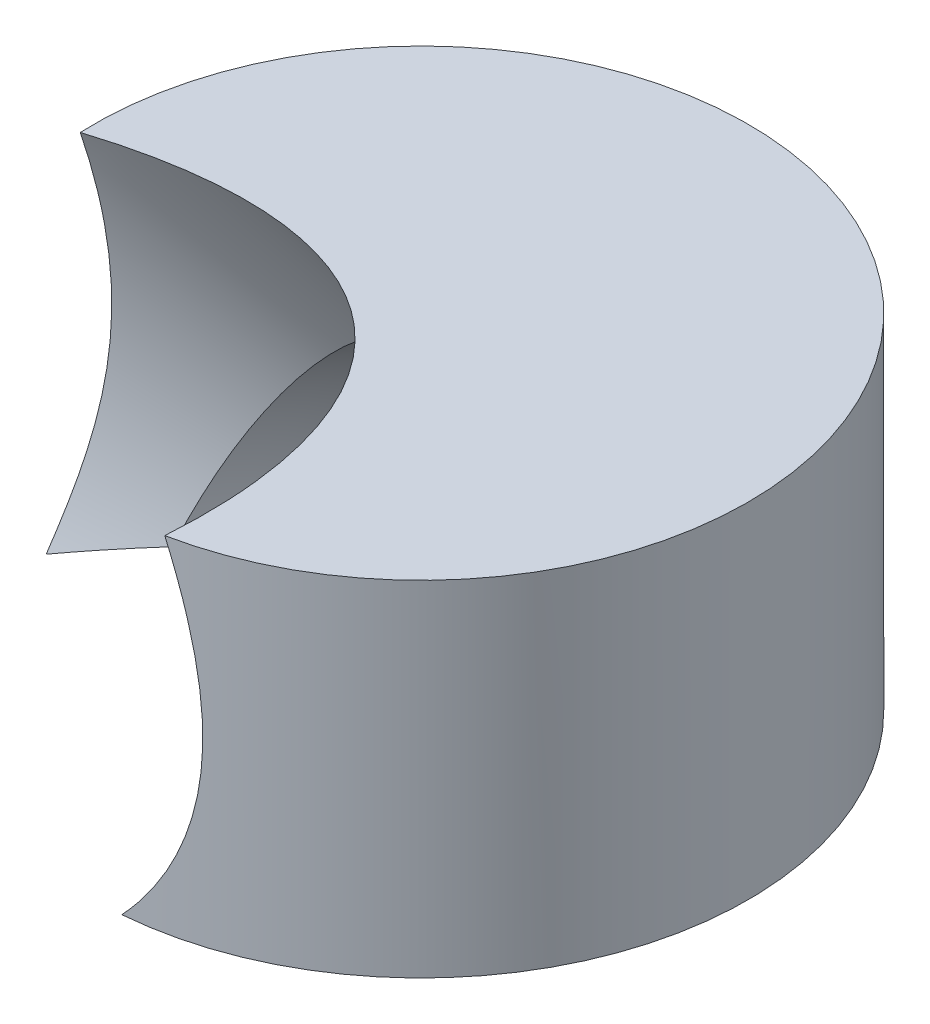
SolidWorks part; units mm, degrees
other "Moving Steel Cup Liner 2"
ref_plane "Front Plane" through (0, 0, 0) normal (0, 0, 1) x (1, 0, 0)
ref_plane "Top Plane" through (0, 0, 0) normal (0, 1, 0) x (1, 0, 0)
ref_plane "Right Plane" through (0, 0, 0) normal (1, 0, 0) x (0, 0, -1)
sketch3d "Keyed Back Sketch datum points"
  point P0 (-56.2917, -97, 0)
  point P1 (-46.2917, -97, 0)
  point P2 (-56.2917, -97, 10)
ref_plane "Keyed Back Sketch plane" through (0, -97, 0) normal (0, -1, 0) x (-1, 0, 0)
sketch "Keyed Back Sketch" plane through (0, -97, 0) normal (0, -1, 0) x (-1, 0, 0)
  line L0 (29.791, 11.2357) -> (33.8308, 13.5681)
  arc A0 (33.8308, 13.5681) -> (29.791, 11.2357) centre (30.3109, 15) ccw
extrude "Keyed Back" add sketch "Keyed Back Sketch" along normal blind 0.7 separate body
sketch3d "Cup Blank Sketch datum points"
  point P0 (-56.2917, -97.7, 0)
  point P1 (-46.2917, -97.7, 0)
  point P2 (-56.2917, -97.7, 10)
ref_plane "Cup Blank Sketch plane" through (0, -97.7, 0) normal (0, -1, 0) x (-1, 0, 0)
sketch "Cup Blank Sketch" plane through (0, -97.7, 0) normal (0, -1, 0) x (-1, 0, 0)
  circle A0 centre (30.3109, 15) radius 3.8
extrude "Cup Blank" add sketch "Cup Blank Sketch" along normal blind 3.3
sketch3d "Spherical Bearing Seat axis line"
  line L0 (-30.3109, -101, -25) -> (-30.3109, -101, -5) construction
ref_axis "Spherical Bearing Seat axis" through (-30.3109, -101, -25) along (0, 0, 1)
sketch3d "Spherical Bearing Seat profile datum points"
  point P0 (-30.3109, -101, -15)
  point P1 (-20.3109, -101, -15)
  point P2 (-30.3109, -101, -5)
ref_plane "Spherical Bearing Seat profile plane" through (0, -101, 0) normal (0, -1, 0) x (-1, 0, 0)
sketch "Spherical Bearing Seat profile" plane through (0, -101, 0) normal (0, -1, 0) x (-1, 0, 0)
  line L0 (30.3109, 11.9) -> (30.3109, 18.1)
  arc A0 (30.3109, 18.1) -> (30.3109, 11.9) centre (30.3109, 15) ccw
revolve "Spherical Bearing Seat" cut sketch "Spherical Bearing Seat profile" angle 360 about axis through (-30.3109, -101, -25) along (0, 0, 1)
sketch3d "Articulation Throat axis line"
  line L0 (-25.111, -106.3831, -21.632) -> (-35.5108, -95.6169, -8.368) construction
ref_axis "Articulation Throat axis" through (-25.111, -106.3831, -21.632) along (-0.52, 0.5383, 0.6632)
sketch3d "Articulation Throat Sketch datum points"
  point P0 (-30.3109, -101, -15)
  point P1 (-30.3109, -93.2358, -21.3021)
  point P2 (-35.5108, -95.6169, -8.368)
ref_plane "Articulation Throat Sketch plane" through (-55.5594, -21.3154, -26.2607) normal (0.8542, 0.3277, 0.4037) x (0.3769, 0.1446, -0.9149)
sketch "Articulation Throat Sketch" plane through (-55.5594, -21.3154, -26.2607) normal (0.8542, 0.3277, 0.4037) x (0.3769, 0.1446, -0.9149)
  line L0 (-12.3085, -83.4412) -> (-10.7241, -81.7739)
  line L1 (-10.7241, -81.7739) -> (-22.7679, -61.059)
  line L2 (-22.7679, -61.059) -> (-28.9813, -67.5977)
  line L3 (-28.9813, -67.5977) -> (-12.3085, -83.4412)
revolve "Articulation Throat" cut sketch "Articulation Throat Sketch" angle 360 about axis through (-25.111, -106.3831, -21.632) along (-0.52, 0.5383, 0.6632)
